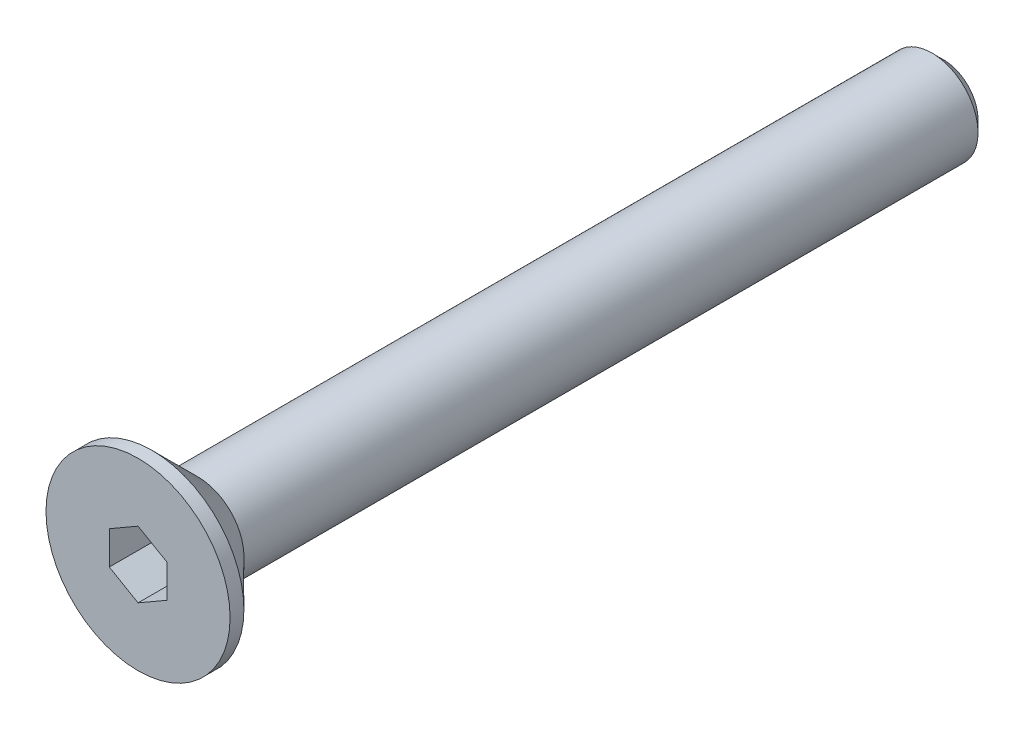
SolidWorks part; units mm, degrees
ref_plane "前视基准面" through (0, 0, 0) normal (0, 0, 1) x (1, 0, 0)
ref_plane "上视基准面" through (0, 0, 0) normal (0, 1, 0) x (1, 0, 0)
ref_plane "右视基准面" through (0, 0, 0) normal (1, 0, 0) x (0, 0, -1)
sketch "草图1" plane through (0, 0, 0) normal (1, 0, 0) x (0, 0, -1)
  line L0 (-17.5, 0) -> (-17.5, 4)
  line L1 (-17.5, 4) -> (-16.9, 4)
  line L2 (-16.9, 4) -> (-14.9, 2)
  line L3 (-14.9, 2) -> (17.5, 2)
  line L5 (17.5, 2) -> (17.5, 0)
  line L6 (17.5, 0) -> (-17.5, 0)
  dimension "D1" = 45
  dimension "D2" = 2
  dimension "D3" = 35
  dimension "D4" = 4
  dimension "D5" = 2.6
revolve "旋转1" add sketch "草图1" angle 360 about L6
chamfer "倒角1" distance 0.5 angle 45 1 edges at (-2, 0, -17.5)
sketch "草图2" plane through (0, 0, 17.5) normal (0, 0, 1) x (1, 0, 0)
  line L1 (0, 1.4434) -> (-1.25, 0.7217)
  line L2 (-1.25, 0.7217) -> (-1.25, -0.7217)
  line L3 (-1.25, -0.7217) -> (0, -1.4434)
  line L4 (0, -1.4434) -> (1.25, -0.7217)
  line L5 (1.25, -0.7217) -> (1.25, 0.7217)
  line L6 (1.25, 0.7217) -> (0, 1.4434)
  circle A0 centre (0, 0) radius 1.25 construction
  dimension "D1" = 2.5
extrude "切除-拉伸1" cut sketch "草图2" against normal blind 2.5
